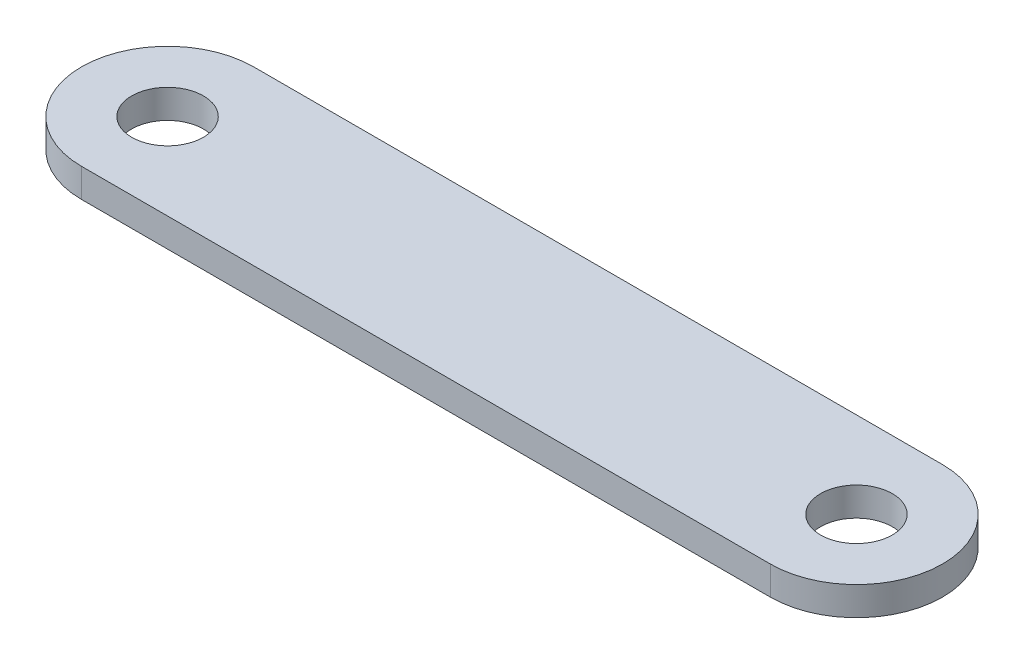
SolidWorks part; units mm, degrees
material "6063-O"
ref_plane "Front Plane" through (0, 0, 0) normal (0, 0, 1) x (1, 0, 0)
ref_plane "Top Plane" through (0, 0, 0) normal (0, 1, 0) x (1, 0, 0)
ref_plane "Right Plane" through (0, 0, 0) normal (1, 0, 0) x (0, 0, -1)
sketch "Sketch1" plane through (0, 0, 0) normal (0, 1, 0) x (1, 0, 0)
  line L0 (-38.1, 0) -> (38.1, 0) construction
  line L1 (-1.7463, 0) -> (1.7463, 0) construction
  line L2 (-38.1, 9.525) -> (38.1, 9.525)
  line L3 (-38.1, -9.525) -> (38.1, -9.525)
  arc A0 (-38.1, 9.525) -> (-38.1, -9.525) centre (-38.1, 0) ccw
  arc A1 (38.1, -9.525) -> (38.1, 9.525) centre (38.1, 0) ccw
  circle A2 centre (-38.1, 0) radius 3.9687
  circle A3 centre (38.1, 0) radius 3.9687
  point P5 (0, 0)
  dimension "D2" = 9.525
  dimension "D3" = 7.9375
  dimension "D1" = 76.2
extrude "Boss-Extrude1" add sketch "Sketch1" along normal mid plane 3.175
